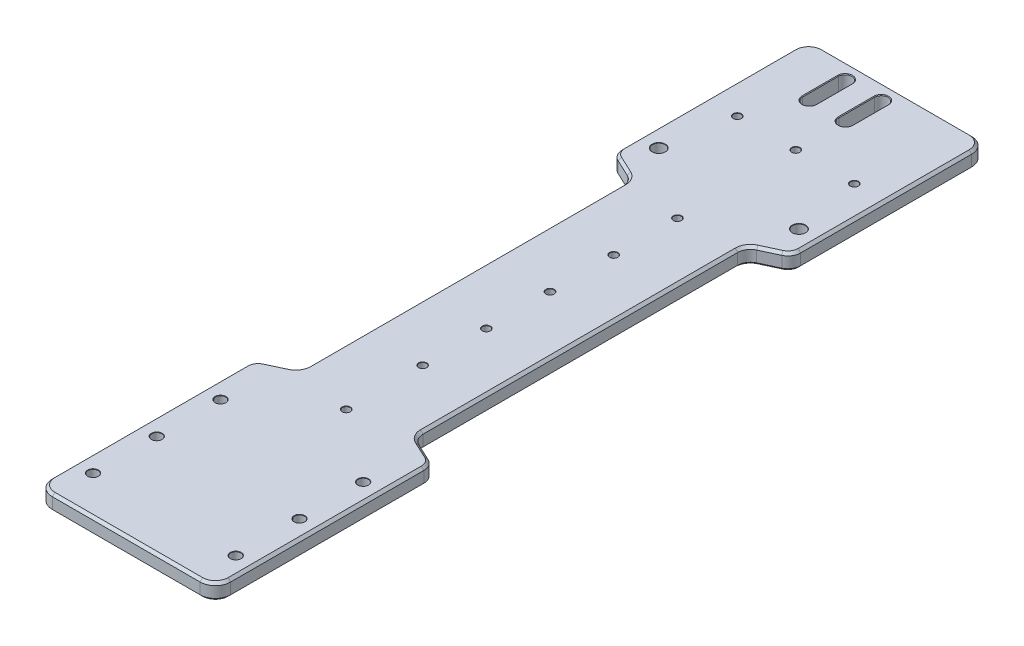
SolidWorks part; units mm, degrees
ref_plane "Front Plane" through (0, 0, 0) normal (0, 0, 1) x (1, 0, 0)
ref_plane "Top Plane" through (0, 0, 0) normal (0, 1, 0) x (1, 0, 0)
ref_plane "Right Plane" through (0, 0, 0) normal (1, 0, 0) x (0, 0, -1)
sketch "Sketch1" plane through (0, 0, 0) normal (0, 1, 0) x (1, 0, 0)
  line L0 (-35, -42) -> (35, -42) construction
  line L1 (35, 122) -> (-35, 122)
  line L2 (35, 122) -> (35, 107.6854)
  line L3 (35, -122) -> (-35, -122)
  line L4 (-35, 122) -> (-35, 107.6854)
  line L5 (35, 122) -> (-35, -122) construction
  line L6 (35, -122) -> (-35, 122) construction
  line L7 (-35, -42) -> (35, -42) construction
  line L8 (-25.3869, -32.5173) -> (-32.1131, -35.6538)
  line L9 (-22.5, -27.9858) -> (-22.5, 95.4858)
  line L10 (-25.3869, 100.0173) -> (-32.1131, 103.1538)
  line L11 (-35, -40.1854) -> (-35, -122)
  line L12 (35, 107) -> (-35, 107) construction
  line L13 (35, 107) -> (-35, 107) construction
  line L14 (0, 122) -> (0, -122) construction
  line L15 (25.3869, -32.5173) -> (32.1131, -35.6538)
  line L16 (22.5, -27.9858) -> (22.5, 95.4858)
  line L17 (25.3869, 100.0173) -> (32.1131, 103.1538)
  line L18 (35, -40.1854) -> (35, -122)
  arc A0 (-32.1131, -35.6538) -> (-35, -40.1854) centre (-30, -40.1854) ccw
  arc A1 (-25.3869, -32.5173) -> (-22.5, -27.9858) centre (-27.5, -27.9858) ccw
  arc A2 (-22.5, 95.4858) -> (-25.3869, 100.0173) centre (-27.5, 95.4858) ccw
  arc A3 (-32.1131, 103.1538) -> (-35, 107.6854) centre (-30, 107.6854) cw
  arc A4 (32.1131, -35.6538) -> (35, -40.1854) centre (30, -40.1854) cw
  arc A5 (25.3869, -32.5173) -> (22.5, -27.9858) centre (27.5, -27.9858) cw
  arc A6 (22.5, 95.4858) -> (25.3869, 100.0173) centre (27.5, 95.4858) cw
  arc A7 (32.1131, 103.1538) -> (35, 107.6854) centre (30, 107.6854) ccw
  point P0 (0, 0)
  point P16 (-35, -37)
  point P23 (-35, 104.5)
  dimension "D7" = 5
  dimension "D1" = 70
  dimension "D2" = 244
  dimension "D3" = 5
  dimension "D4" = 115
  dimension "D5" = 115
  dimension "D6" = 2.5
  dimension "D8" = 22.5
extrude "Boss-Extrude1" add sketch "Sketch1" along normal blind 6.35
sketch "Sketch3" plane through (0, 0, -122) normal (0, 0, -1) x (-1, 0, 0)
  line L8 (-35, 0) -> (35, 0)
  line L9 (35, 0) -> (35, 6.35)
  line L10 (35, 6.35) -> (-35, 6.35)
  line L11 (-35, 6.35) -> (-35, 0)
  line L12 (-35, 0) -> (35, 0)
  line L13 (35, 0) -> (35, 6.35)
  line L14 (35, 6.35) -> (-35, 6.35)
  line L15 (-35, 6.35) -> (-35, 0)
  dimension "D1" = 0
extrude "Boss-Extrude2" add sketch "Sketch3" along normal up to surface (58.8 mm away)
hole_wizard "Ø4.0mm Dowel Hole1" positions "Sketch4" profile "Sketch5" hole size "Ø4.0" standard "ANSI Metric" end condition through all
sketch "Sketch4" plane through (0, 0, 0) normal (0, -1, 0) x (-1, 0, 0)
  point P0 (28, -57)
  point P3 (28, -82)
  point P6 (28, -107)
  point P9 (-28, -107)
  point P12 (-28, -82)
  point P15 (-28, -57)
sketch "Sketch5" plane through (-28, 0, 57) normal (1, 0, 0) x (0, 0, -1)
  line L0 (0, 0) -> (0, 6.35)
  line L1 (0, 6.35) -> (2.125, 6.35)
  line L2 (2, 6.225) -> (2, 0.125)
  line L3 (2, 0.125) -> (2.125, 0)
  line L5 (2.125, 0) -> (0, 0)
  line L6 (-2, 0.125) -> (-2.125, 0) construction
  line L7 (2.125, 6.35) -> (2, 6.225)
  line L8 (-2.125, 6.35) -> (-2, 6.225) construction
  line L11 (0, -6.35) -> (0, 107.95) construction
  dimension "Thru Hole Dia." = 4
  dimension "Thru Hole Depth" = 6.35
  dimension "Near C'Sink Dia." = 4.25
  dimension "Near C'Sink Angle" = 90
  dimension "Far C'Sink Dia." = 4.25
  dimension "Far C'Sink Angle" = 90
hole_wizard "Ø3.0mm Dowel Hole1" positions "Sketch6" profile "Sketch7" hole size "Ø3.0" standard "ANSI Metric" end condition through all
sketch "Sketch6" plane through (0, 6.35, 0) normal (0, 1, 0) x (1, 0, 0)
  point P0 (0, 94.3212)
  point P3 (0, 69.3212)
  point P6 (0, 44.3212)
  point P9 (0, 19.3212)
  point P12 (0, -5.6788)
  point P15 (0, -5.6788)
  point P17 (0, -35.6788)
sketch "Sketch7" plane through (0, 6.35, -94.3212) normal (1, 0, 0) x (0, 0, 1)
  line L0 (0, 0) -> (0, 6.35)
  line L1 (0, 6.35) -> (1.625, 6.35)
  line L2 (1.5, 6.225) -> (1.5, 0.125)
  line L3 (1.5, 0.125) -> (1.625, 0)
  line L5 (1.625, 0) -> (0, 0)
  line L6 (-1.5, 0.125) -> (-1.625, 0) construction
  line L7 (1.625, 6.35) -> (1.5, 6.225)
  line L8 (-1.625, 6.35) -> (-1.5, 6.225) construction
  line L11 (0, -6.35) -> (0, 107.95) construction
  dimension "Thru Hole Dia." = 3
  dimension "Thru Hole Depth" = 6.35
  dimension "Near C'Sink Dia." = 3.25
  dimension "Near C'Sink Angle" = 90
  dimension "Far C'Sink Dia." = 3.25
  dimension "Far C'Sink Angle" = 90
hole_wizard "Ø5.0mm Dowel Hole1" positions "Sketch8" profile "Sketch9" hole size "Ø5.0" standard "ANSI Metric" end condition through all
sketch "Sketch8" plane through (0, 6.35, 0) normal (0, 1, 0) x (1, 0, 0)
  point P0 (27.5, 114.5)
  point P3 (-27.5, 114.5)
sketch "Sketch9" plane through (27.5, 6.35, -114.5) normal (1, 0, 0) x (0, 0, 1)
  line L0 (0, 0) -> (0, 6.35)
  line L1 (0, 6.35) -> (2.625, 6.35)
  line L2 (2.5, 6.225) -> (2.5, 0.125)
  line L3 (2.5, 0.125) -> (2.625, 0)
  line L5 (2.625, 0) -> (0, 0)
  line L6 (-2.5, 0.125) -> (-2.625, 0) construction
  line L7 (2.625, 6.35) -> (2.5, 6.225)
  line L8 (-2.625, 6.35) -> (-2.5, 6.225) construction
  line L11 (0, -6.35) -> (0, 107.95) construction
  dimension "Thru Hole Dia." = 5
  dimension "Thru Hole Depth" = 6.35
  dimension "Near C'Sink Dia." = 5.25
  dimension "Near C'Sink Angle" = 90
  dimension "Far C'Sink Dia." = 5.25
  dimension "Far C'Sink Angle" = 90
sketch "Sketch10" plane through (0, 6.35, 0) normal (0, 1, 0) x (1, 0, 0)
  line L0 (-14.2, 174.3) -> (-14.2, 160.3) construction
  line L1 (-11.55, 174.3) -> (-11.55, 160.3)
  line L2 (-16.85, 174.3) -> (-16.85, 160.3)
  line L3 (0, 174.3) -> (0, 160.3) construction
  line L4 (2.65, 174.3) -> (2.65, 160.3)
  line L5 (-2.65, 174.3) -> (-2.65, 160.3)
  arc A0 (-11.55, 174.3) -> (-16.85, 174.3) centre (-14.2, 174.3) ccw
  arc A1 (-16.85, 160.3) -> (-11.55, 160.3) centre (-14.2, 160.3) ccw
  arc A2 (2.65, 174.3) -> (-2.65, 174.3) centre (0, 174.3) ccw
  arc A3 (-2.65, 160.3) -> (2.65, 160.3) centre (0, 160.3) ccw
  point P2 (-14.2, 167.3)
  point P9 (0, 167.3)
  dimension "D2" = 2.65
  dimension "D1" = 14
extrude "Cut-Extrude3" cut sketch "Sketch10" against normal through all
sketch "Sketch12" plane through (0, 0, 0) normal (0, -1, 0) x (1, 0, 0)
  line L0 (-35, -107.6854) -> (35, -180.8) construction
  line L1 (0, -144.2427) -> (0, -138.2427) construction
  line L3 (24, -120.7427) -> (-24, -120.7427)
  line L4 (30, -126.7427) -> (30, -149.7427)
  line L5 (24, -155.7427) -> (-24, -155.7427)
  line L6 (-30, -126.7427) -> (-30, -149.7427)
  line L7 (30, -120.7427) -> (-30, -155.7427) construction
  line L8 (30, -155.7427) -> (-30, -120.7427) construction
  arc A0 (-24, -120.7427) -> (-30, -126.7427) centre (-24, -126.7427) ccw
  arc A1 (-24, -155.7427) -> (-30, -149.7427) centre (-24, -149.7427) cw
  arc A2 (30, -149.7427) -> (24, -155.7427) centre (24, -149.7427) cw
  arc A3 (24, -120.7427) -> (30, -126.7427) centre (24, -126.7427) cw
  dimension "D4" = 6
  dimension "D1" = 35
  dimension "D2" = 60
  dimension "D3" = 6
extrude "Cut-Extrude4" cut sketch "Sketch12" against normal blind 2.5
hole_wizard "Ø3.0mm Dowel Hole2" positions "Sketch14" profile "Sketch15" hole size "Ø3.0" standard "ANSI Metric" end condition through all
sketch "Sketch14" plane through (0, 2.5, 0) normal (0, -1, 0) x (-1, 0, 0)
  line L0 (-30, 149.7427) -> (-30, 126.7427) construction
  line L1 (24, 155.7427) -> (-24, 155.7427) construction
  line L2 (-23, 140.7427) -> (22.944, 140.7427) construction
  point P0 (22.944, 140.7427)
  point P2 (-0.028, 140.7427)
  point P4 (-23, 140.7427)
  dimension "D1" = 7
  dimension "D2" = 15
  dimension "D3" = 45.944
sketch "Sketch15" plane through (-22.944, 2.5, -140.7427) normal (1, 0, 0) x (0, 0, -1)
  line L0 (0, 0) -> (0, 3.85)
  line L1 (0, 3.85) -> (1.625, 3.85)
  line L2 (1.5, 3.725) -> (1.5, 0.125)
  line L3 (1.5, 0.125) -> (1.625, 0)
  line L5 (1.625, 0) -> (0, 0)
  line L6 (-1.5, 0.125) -> (-1.625, 0) construction
  line L7 (1.625, 3.85) -> (1.5, 3.725)
  line L8 (-1.625, 3.85) -> (-1.5, 3.725) construction
  line L11 (0, -6.35) -> (0, 107.95) construction
  dimension "Thru Hole Dia." = 3
  dimension "Thru Hole Depth" = 3.85
  dimension "Near C'Sink Dia." = 3.25
  dimension "Near C'Sink Angle" = 90
  dimension "Far C'Sink Dia." = 3.25
  dimension "Far C'Sink Angle" = 90
fillet "Fillet1" radius 6 4 edges at (-35, 3.175, 122) (35, 3.175, 122) (35, 3.175, -180.8) (-35, 3.175, -180.8)
chamfer "Chamfer8" distance 1 angle 45 48 edges at (-35, 6.35, 78.0927) (-33.2426, 6.35, 120.2426) (-34.217, 6.35, 37.4989) (0, 6.35, 122) (-28.75, 6.35, 34.0856) (33.2426, 6.35, 120.2426) (-23.283, 6.35, 30.6723) (35, 6.35, 78.0927) (-22.5, 6.35, -33.75) (34.217, 6.35, 37.4989) (-23.283, 6.35, -98.1723) (28.75, 6.35, 34.0856) (-28.75, 6.35, -101.5856) (23.283, 6.35, 30.6723) (-34.217, 6.35, -104.9989) (22.5, 6.35, -33.75) (-35, 6.35, -141.2427) (23.283, 6.35, -98.1723) (-33.2426, 6.35, -179.0426) (28.75, 6.35, -101.5856) (0, 6.35, -180.8) (34.217, 6.35, -104.9989) (33.2426, 6.35, -179.0426) (35, 6.35, -141.2427) (-35, 0, 78.0927) (-33.2426, 0, 120.2426) (-34.217, 0, 37.4989) (0, 0, 122) (-28.75, 0, 34.0856) (33.2426, 0, 120.2426) (-23.283, 0, 30.6723) (35, 0, 78.0927) (-22.5, 0, -33.75) (34.217, 0, 37.4989) (-23.283, 0, -98.1723) (28.75, 0, 34.0856) (-28.75, 0, -101.5856) (23.283, 0, 30.6723) (-34.217, 0, -104.9989) (22.5, 0, -33.75) (-35, 0, -141.2427) (23.283, 0, -98.1723) (-33.2426, 0, -179.0426) (28.75, 0, -101.5856) (0, 0, -180.8) (34.217, 0, -104.9989) (33.2426, 0, -179.0426) (35, 0, -141.2427)
chamfer "Chamfer11" distance 0.25 angle 45 24 edges at (-16.85, 6.35, -167.3) (-14.2, 6.35, -157.65) (-14.2, 6.35, -176.95) (-11.55, 6.35, -167.3) (-2.65, 6.35, -167.3) (0, 6.35, -157.65) (0, 6.35, -176.95) (2.65, 6.35, -167.3) (0, 0, -120.7427) (-28.2426, 0, -122.5) (28.2426, 0, -122.5) (-30, 0, -138.2427) (30, 0, -138.2427) (-28.2426, 0, -153.9853) (28.2426, 0, -153.9853) (0, 0, -155.7427) (2.65, 0, -167.3) (0, 0, -176.95) (0, 0, -157.65) (-2.65, 0, -167.3) (-11.55, 0, -167.3) (-14.2, 0, -176.95) (-14.2, 0, -157.65) (-16.85, 0, -167.3)
